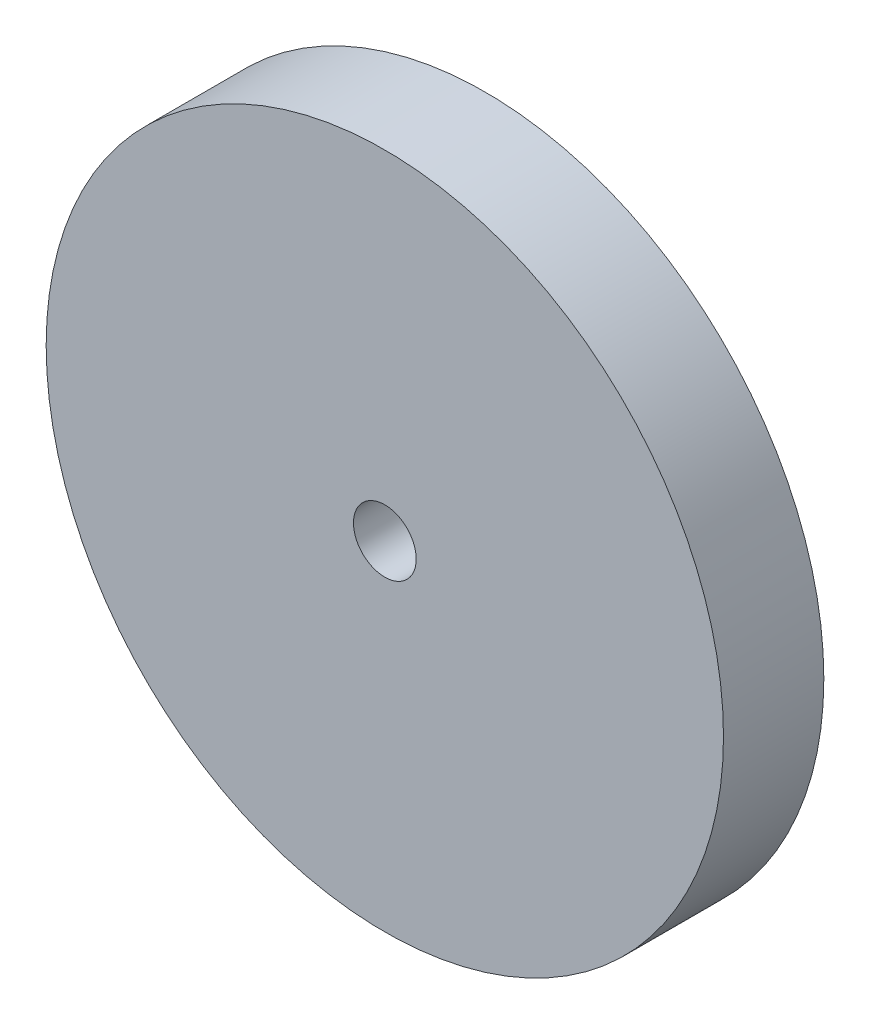
SolidWorks part; units mm, degrees
ref_plane "Front Plane" through (0, 0, 0) normal (0, 0, 1) x (1, 0, 0)
ref_plane "Top Plane" through (0, 0, 0) normal (0, 1, 0) x (1, 0, 0)
ref_plane "Right Plane" through (0, 0, 0) normal (1, 0, 0) x (0, 0, -1)
sketch "Sketch1" plane through (0, 0, 0) normal (0, 0, 1) x (1, 0, 0)
  circle A0 centre (0, 0) radius 27
  circle A1 centre (0, 0) radius 2.5
  dimension "D1" = 54
  dimension "D2" = 5
extrude "Boss-Extrude1" add sketch "Sketch1" along normal blind 8
